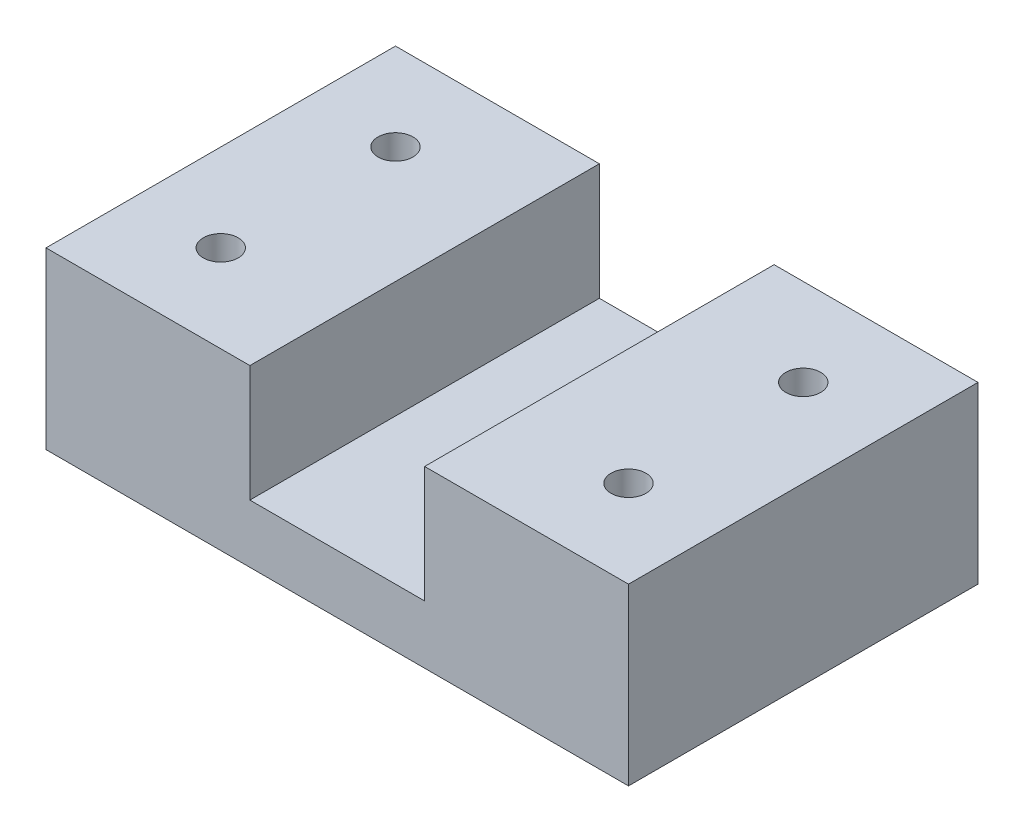
SolidWorks part; units mm, degrees
ref_plane "Front Plane" through (0, 0, 0) normal (0, 0, 1) x (1, 0, 0)
ref_plane "Top Plane" through (0, 0, 0) normal (0, 1, 0) x (1, 0, 0)
ref_plane "Right Plane" through (0, 0, 0) normal (1, 0, 0) x (0, 0, -1)
sketch "Sketch2" plane through (0, 0, 0) normal (0, 1, 0) x (1, 0, 0)
  line L1 (-2.5, 1.5) -> (2.5, 1.5)
  line L2 (-2.5, 1.5) -> (-2.5, -1.5)
  line L3 (-2.5, -1.5) -> (2.5, -1.5)
  line L4 (2.5, 1.5) -> (2.5, -1.5)
  line L5 (-2.5, 1.5) -> (2.5, -1.5) construction
  line L6 (-2.5, -1.5) -> (2.5, 1.5) construction
  point P0 (0, 0)
  dimension "D1" = 5
  dimension "D2" = 3
extrude "Boss-Extrude1" add sketch "Sketch2" along normal blind 0.5
sketch "Sketch3" plane through (0, 0, 0) normal (0, 1, 0) x (1, 0, 0)
  line L0 (-2.5, -1.5) -> (2.5, -1.5) construction
  line L1 (-2.5, 1.5) -> (-0.75, 1.5)
  line L2 (-2.5, 1.5) -> (-2.5, -1.5)
  line L3 (-2.5, -1.5) -> (-0.75, -1.5)
  line L4 (-0.75, 1.5) -> (-0.75, -1.5)
  line L6 (2.5, 1.5) -> (0.75, 1.5)
  line L7 (2.5, 1.5) -> (2.5, -1.5)
  line L8 (2.5, -1.5) -> (0.75, -1.5)
  line L9 (0.75, 1.5) -> (0.75, -1.5)
  dimension "D1" = 1.5
  dimension "D2" = 0.75
extrude "Boss-Extrude2" add sketch "Sketch3" along normal blind 1.5
sketch "Sketch4" plane through (0, 0, 0) normal (0, 1, 0) x (1, 0, 0)
  line L0 (0, 1.5962) -> (0, -1.6789) construction
  line L1 (-2.8286, 0) -> (2.7348, 0) construction
  line L2 (-0.75, 1.5) -> (-2.5, 1.5) construction
  line L3 (-2.5, 1.5) -> (-2.5, -1.5) construction
  circle A0 centre (-1.75, 0.75) radius 0.15
  circle A1 centre (1.75, 0.75) radius 0.15
  circle A2 centre (1.75, -0.75) radius 0.15
  circle A3 centre (-1.75, -0.75) radius 0.15
  dimension "D1" = 0.3
  dimension "D2" = 0.75
  dimension "D3" = 0.75
extrude "Cut-Extrude1" cut sketch "Sketch4" along normal blind 0.5 and the other way through all from offset 1
